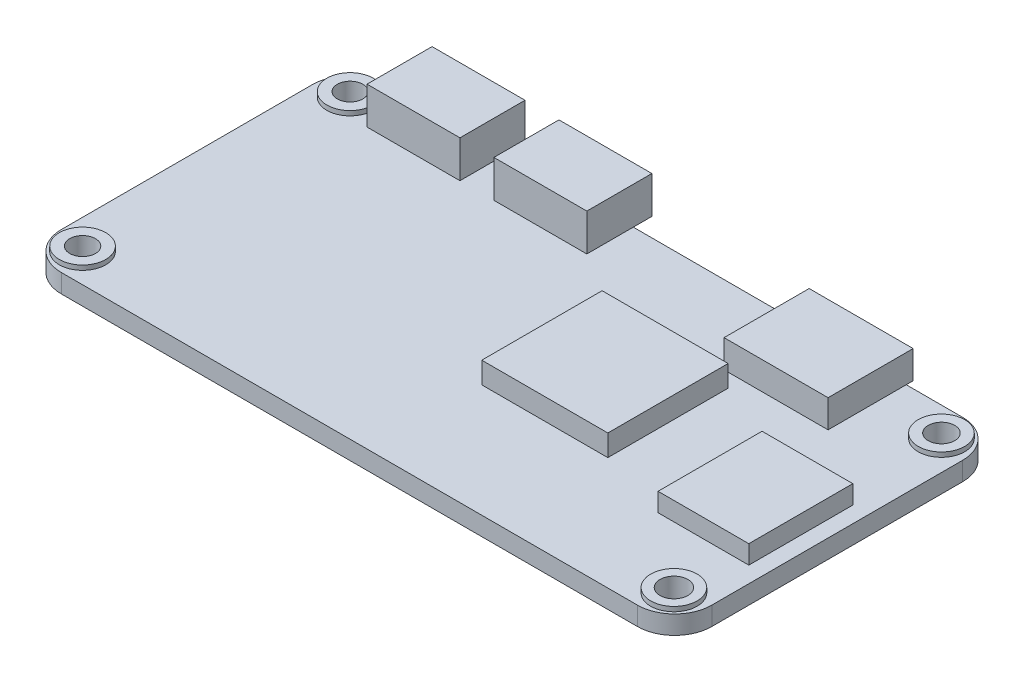
SolidWorks part; units mm, degrees
ref_plane "Front Plane" through (0, 0, 0) normal (0, 0, 1) x (1, 0, 0)
ref_plane "Top Plane" through (0, 0, 0) normal (0, 1, 0) x (1, 0, 0)
ref_plane "Right Plane" through (0, 0, 0) normal (1, 0, 0) x (0, 0, -1)
sketch "Sketch1" plane through (0, 0, 0) normal (0, 1, 0) x (1, 0, 0)
  line L1 (-31, 17.5) -> (31, 17.5)
  line L2 (-35, 13.5) -> (-35, -13.5)
  line L3 (-31, -17.5) -> (31, -17.5)
  line L4 (35, 13.5) -> (35, -13.5)
  line L5 (-35, 17.5) -> (35, -17.5) construction
  line L6 (-35, -17.5) -> (35, 17.5) construction
  arc A0 (-35, -13.5) -> (-31, -17.5) centre (-31, -13.5) ccw
  arc A1 (31, -17.5) -> (35, -13.5) centre (31, -13.5) ccw
  arc A2 (31, 17.5) -> (35, 13.5) centre (31, 13.5) cw
  arc A3 (-31, 17.5) -> (-35, 13.5) centre (-31, 13.5) ccw
  point P0 (0, 0)
  dimension "D1" = 70
  dimension "D3" = 4
  dimension "D2" = 35
extrude "Boss-Extrude1" add sketch "Sketch1" along normal blind 2
sketch "Sketch2" plane through (0, 2, 0) normal (0, 1, 0) x (1, 0, 0)
  line L1 (31.8182, -14.3939) -> (-31.8182, -14.3939) construction
  line L2 (31.8182, -14.3939) -> (31.8182, 14.3939) construction
  line L3 (31.8182, 14.3939) -> (-31.8182, 14.3939) construction
  line L4 (-31.8182, -14.3939) -> (-31.8182, 14.3939) construction
  line L5 (31.8182, -14.3939) -> (-31.8182, 14.3939) construction
  line L6 (31.8182, 14.3939) -> (-31.8182, -14.3939) construction
  circle A0 centre (31.8182, -14.3939) radius 2.5
  circle A1 centre (-31.8182, -14.3939) radius 2.5
  circle A2 centre (-31.8182, 14.3939) radius 2.5
  circle A3 centre (31.8182, 14.3939) radius 2.5
  point P0 (0, 0)
  dimension "D1" = 5
extrude "Boss-Extrude2" add sketch "Sketch2" along normal blind 0.5
sketch "Sketch3" plane through (0, 2, 0) normal (0, 1, 0) x (1, 0, 0)
  line L1 (31.8182, -14.3939) -> (-31.8182, -14.3939) construction
  line L2 (31.8182, -14.3939) -> (31.8182, 14.3939) construction
  line L3 (31.8182, 14.3939) -> (-31.8182, 14.3939) construction
  line L4 (-31.8182, -14.3939) -> (-31.8182, 14.3939) construction
  line L5 (31.8182, -14.3939) -> (-31.8182, 14.3939) construction
  line L6 (31.8182, 14.3939) -> (-31.8182, -14.3939) construction
  circle A0 centre (31.8182, -14.3939) radius 1.5
  circle A1 centre (-31.8182, -14.3939) radius 1.387
  circle A2 centre (-31.8182, 14.3939) radius 1.3739
  circle A3 centre (31.8182, 14.3939) radius 1.4287
  point P0 (0, 0)
  dimension "D1" = 3
extrude "Cut-Extrude1" cut sketch "Sketch3" against normal through all and the other way through all
sketch "Sketch4" plane through (0, 2, 0) normal (0, 1, 0) x (1, 0, 0)
  line L1 (15.6623, -5.3507) -> (2.0968, -5.3507)
  line L2 (15.6623, -5.3507) -> (15.6623, 7.5981)
  line L3 (15.6623, 7.5981) -> (2.0968, 7.5981)
  line L4 (2.0968, -5.3507) -> (2.0968, 7.5981)
  line L5 (15.6623, -5.3507) -> (2.0968, 7.5981) construction
  line L6 (15.6623, 7.5981) -> (2.0968, -5.3507) construction
  point P0 (8.8795, 1.1237)
extrude "Boss-Extrude3" add sketch "Sketch4" along normal blind 2.3
sketch "Sketch5" plane through (0, 2, 0) normal (0, 1, 0) x (1, 0, 0)
  line L1 (33.266, -7.7824) -> (23.4998, -7.7824)
  line L2 (33.266, -7.7824) -> (33.266, 3.408)
  line L3 (33.266, 3.408) -> (23.4998, 3.408)
  line L4 (23.4998, -7.7824) -> (23.4998, 3.408)
  line L5 (33.266, -7.7824) -> (23.4998, 3.408) construction
  line L6 (33.266, 3.408) -> (23.4998, -7.7824) construction
  point P0 (28.3829, -2.1872)
extrude "Boss-Extrude4" add sketch "Sketch5" along normal blind 2
sketch "Sketch6" plane through (0, 2, 0) normal (0, 1, 0) x (1, 0, 0)
  line L0 (31, 17.5) -> (-31, 17.5) construction
  line L1 (-4.4466, 12.5) -> (-14.4466, 12.5)
  line L2 (-4.4466, 12.5) -> (-4.4466, 19.5)
  line L3 (-4.4466, 19.5) -> (-14.4466, 19.5)
  line L4 (-14.4466, 12.5) -> (-14.4466, 19.5)
  line L5 (-4.4466, 12.5) -> (-14.4466, 19.5) construction
  line L6 (-4.4466, 19.5) -> (-14.4466, 12.5) construction
  line L7 (-18.1012, 12.5) -> (-28.1012, 12.5)
  line L8 (-18.1012, 12.5) -> (-18.1012, 19.5)
  line L9 (-18.1012, 19.5) -> (-28.1012, 19.5)
  line L10 (-28.1012, 12.5) -> (-28.1012, 19.5)
  line L11 (-18.1012, 12.5) -> (-28.1012, 19.5) construction
  line L12 (-18.1012, 19.5) -> (-28.1012, 12.5) construction
  point P0 (-9.4466, 16)
  point P5 (-23.1012, 16)
  dimension "D1" = 2
  dimension "D2" = 2
  dimension "D3" = 5
  dimension "D4" = 5
  dimension "D5" = 10
  dimension "D6" = 10
extrude "Boss-Extrude5" add sketch "Sketch6" along normal blind 4
sketch "Sketch7" plane through (0, 0, -19.5) normal (0, 0, -1) x (-1, 0, 0)
  line L1 (4.7996, 5.5183) -> (13.8762, 5.5183)
  line L2 (4.7996, 5.5183) -> (4.7996, 2.4284)
  line L3 (4.7996, 2.4284) -> (13.8762, 2.4284)
  line L4 (13.8762, 5.5183) -> (13.8762, 2.4284)
  line L5 (4.7996, 5.5183) -> (13.8762, 2.4284) construction
  line L6 (4.7996, 2.4284) -> (13.8762, 5.5183) construction
  line L7 (18.8007, 5.5183) -> (27.5876, 5.5183)
  line L8 (18.8007, 5.5183) -> (18.8007, 2.4284)
  line L9 (18.8007, 2.4284) -> (27.5876, 2.4284)
  line L10 (27.5876, 5.5183) -> (27.5876, 2.4284)
  line L11 (18.8007, 5.5183) -> (27.5876, 2.4284) construction
  line L12 (18.8007, 2.4284) -> (27.5876, 5.5183) construction
  point P0 (9.3379, 3.9734)
  point P5 (23.1942, 3.9734)
extrude "Cut-Extrude2" cut sketch "Sketch7" against normal blind 5
sketch "Sketch8" plane through (0, 2, 0) normal (0, 1, 0) x (1, 0, 0)
  line L1 (24.924, 9.0876) -> (13.7337, 9.0876)
  line L2 (24.924, 9.0876) -> (24.924, 18.2434)
  line L3 (24.924, 18.2434) -> (13.7337, 18.2434)
  line L4 (13.7337, 9.0876) -> (13.7337, 18.2434)
  line L5 (24.924, 9.0876) -> (13.7337, 18.2434) construction
  line L6 (24.924, 18.2434) -> (13.7337, 9.0876) construction
  point P0 (19.3288, 13.6655)
extrude "Boss-Extrude6" add sketch "Sketch8" along normal blind 3
